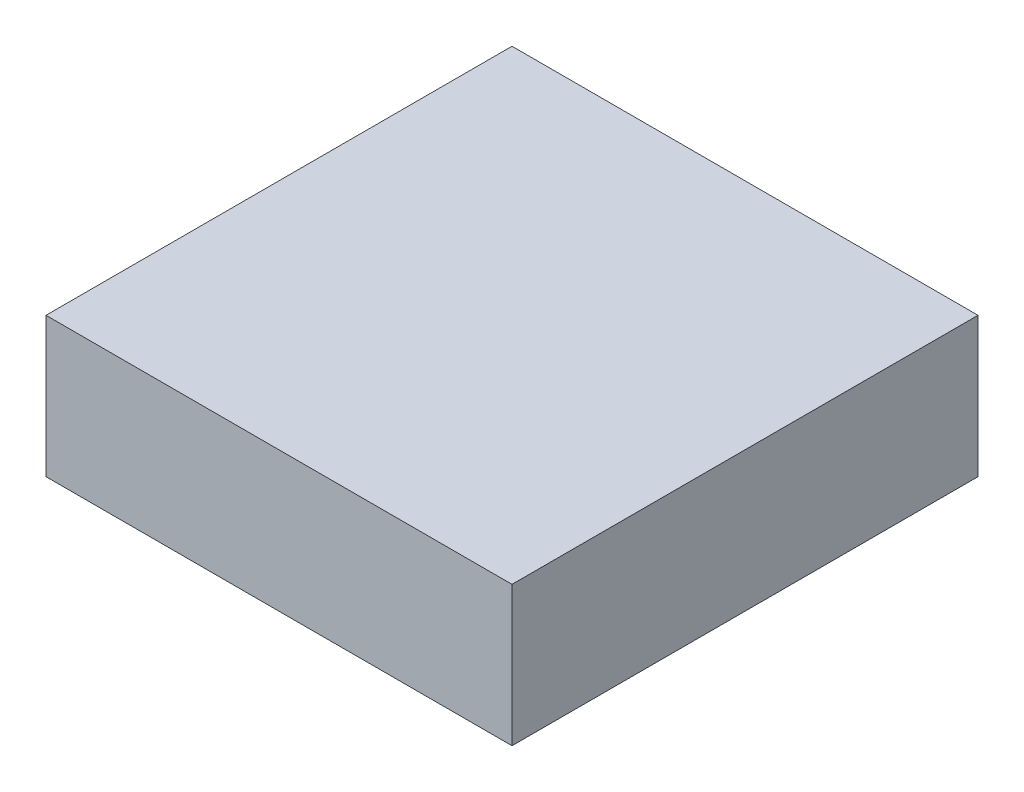
SolidWorks part; units mm, degrees
ref_plane "Front Plane" through (0, 0, 0) normal (0, 0, 1) x (1, 0, 0)
ref_plane "Top Plane" through (0, 0, 0) normal (0, 1, 0) x (1, 0, 0)
ref_plane "Right Plane" through (0, 0, 0) normal (1, 0, 0) x (0, 0, -1)
sketch "Sketch1" plane through (0, 0, 0) normal (0, 1, 0) x (1, 0, 0)
  line L1 (0, 0) -> (500, 0)
  line L2 (0, 0) -> (0, 500)
  line L3 (0, 500) -> (500, 500)
  line L4 (500, 0) -> (500, 500)
  dimension "D1" = 500
extrude "Boss-Extrude1" add sketch "Sketch1" along normal blind 150
